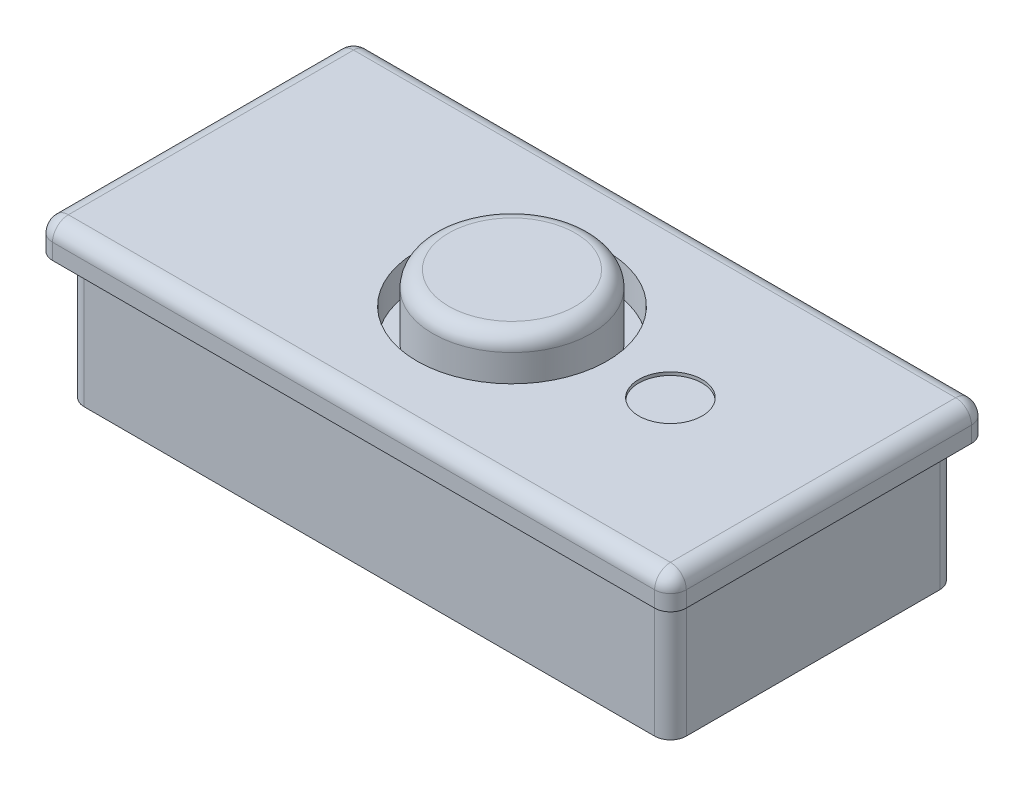
SolidWorks part; units mm, degrees
ref_plane "Front Plane" through (0, 0, 0) normal (0, 0, 1) x (1, 0, 0)
ref_plane "Top Plane" through (0, 0, 0) normal (0, 1, 0) x (1, 0, 0)
ref_plane "Right Plane" through (0, 0, 0) normal (1, 0, 0) x (0, 0, -1)
sketch "Sketch1" plane through (0, 0, 0) normal (0, 1, 0) x (1, 0, 0)
  line L1 (1, 0) -> (39, 0)
  line L2 (0, 1) -> (0, 19)
  line L3 (1, 20) -> (39, 20)
  line L4 (40, 1) -> (40, 19)
  arc A0 (1, 0) -> (0, 1) centre (1, 1) cw
  arc A1 (0, 19) -> (1, 20) centre (1, 19) cw
  arc A2 (39, 20) -> (40, 19) centre (39, 19) cw
  arc A3 (39, 0) -> (40, 1) centre (39, 1) ccw
  circle A4 centre (20, 10) radius 6
  point P7 (0, 0)
  point P10 (0, 20)
  point P15 (40, 0)
  point P18 (0, 0)
  point P19 (0, 10)
  point P20 (0, 0)
  point P21 (20, 0)
  dimension "D3" = 1
  dimension "D4" = 12
  dimension "D1" = 20
  dimension "D2" = 40
extrude "Boss-Extrude1" add sketch "Sketch1" along normal blind 2
sketch "Sketch2" plane through (0, 0, 0) normal (0, 1, 0) x (1, 0, 0)
  line L0 (1, 0) -> (39, 0) construction
  line L1 (2, 1) -> (38, 1)
  line L2 (1, 2) -> (1, 18)
  line L3 (2, 19) -> (38, 19)
  line L4 (39, 2) -> (39, 18)
  line L5 (0, 19) -> (0, 1) construction
  arc A0 (38, 1) -> (39, 2) centre (38, 2) ccw
  arc A1 (39, 18) -> (38, 19) centre (38, 18) ccw
  arc A2 (2, 19) -> (1, 18) centre (2, 18) ccw
  arc A3 (2, 1) -> (1, 2) centre (2, 2) cw
  point P10 (39, 1)
  point P15 (1, 19)
  point P18 (1, 1)
  dimension "D5" = 1
  dimension "D1" = 38
  dimension "D2" = 18
  dimension "D3" = 1
  dimension "D4" = 1
extrude "Boss-Extrude2" add sketch "Sketch2" against normal blind 8
sketch "Sketch3" plane through (0, 0, 0) normal (0, 1, 0) x (1, 0, 0)
  circle A0 centre (20, 10) radius 5
  dimension "D1" = 10
extrude "Boss-Extrude3" add sketch "Sketch3" along normal blind 4
sketch "Sketch4" plane through (0, 2, 0) normal (0, 1, 0) x (1, 0, 0)
  line L0 (40, 1) -> (40, 19) construction
  circle A0 centre (30, 10) radius 2
  circle A1 centre (20, 10) radius 6 construction
  point P2 (0, 0)
  point P3 (0, 0)
  point P6 (40, 10)
  dimension "D1" = 4
  dimension "D2" = 10
extrude "Cut-Extrude1" cut sketch "Sketch4" against normal blind 0.2
fillet "Fillet1" radius 1 9 edges at (39.7071, 2, -0.2929) (20, 2, 0) (0.2929, 2, -0.2929) (0, 2, -10) (0.2929, 2, -19.7071) (20, 2, -20) (39.7071, 2, -19.7071) (40, 2, -10) (20, 4, -5)
